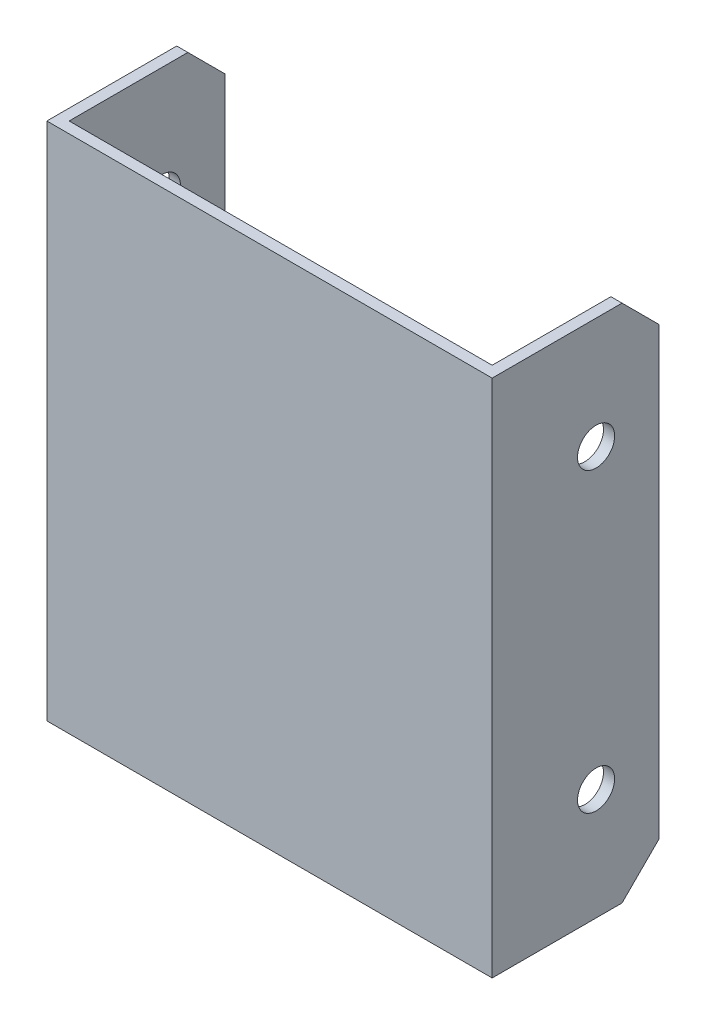
SolidWorks part; units mm, degrees
ref_plane "Front Plane" through (0, 0, 0) normal (0, 0, 1) x (1, 0, 0)
ref_plane "Top Plane" through (0, 0, 0) normal (0, 1, 0) x (1, 0, 0)
ref_plane "Right Plane" through (0, 0, 0) normal (1, 0, 0) x (0, 0, -1)
sketch "Sketch1" plane through (0, 0, 0) normal (0, 1, 0) x (1, 0, 0)
  line L0 (0, 0) -> (60, 0)
  line L1 (60, 0) -> (60, 22.5)
  line L2 (0, 0) -> (0, 22.5)
  line L3 (1.5, 1.5) -> (1.5, 22.5)
  line L4 (1.5, 1.5) -> (58.5, 1.5)
  line L5 (58.5, 1.5) -> (58.5, 22.5)
  line L6 (0, 22.5) -> (1.5, 22.5)
  line L7 (58.5, 22.5) -> (60, 22.5)
  dimension "D1" = 60
  dimension "D2" = 22.5
  dimension "D6" = 1.5
extrude "Boss-Extrude1" add sketch "Sketch1" along normal blind 70 contours L0 L1 L7 L5 L4 L3 L6 L2
ref_plane "Plane1" through (60, 0, 0) normal (1, 0, 0) x (0, 0, -1)
sketch "Sketch3" plane through (60, 0, 0) normal (1, 0, 0) x (0, 0, -1)
  line L0 (0, 70) -> (0, 0) construction
  line L1 (0, 35) -> (22.5, 35) construction
  line L2 (22.5, 70) -> (22.5, 0) construction
  circle A0 centre (14, 55) radius 2.5
  circle A1 centre (14, 15) radius 2.5
  dimension "D1" = 5
  dimension "D2" = 15
  dimension "D3" = 14
extrude "Cut-Extrude1" cut sketch "Sketch3" against normal blind 60
chamfer "Chamfer1" distance 5 angle 45 4 edges at (59.25, 70, -22.5) (0.75, 70, -22.5) (0.75, 0, -22.5) (59.25, 0, -22.5)
